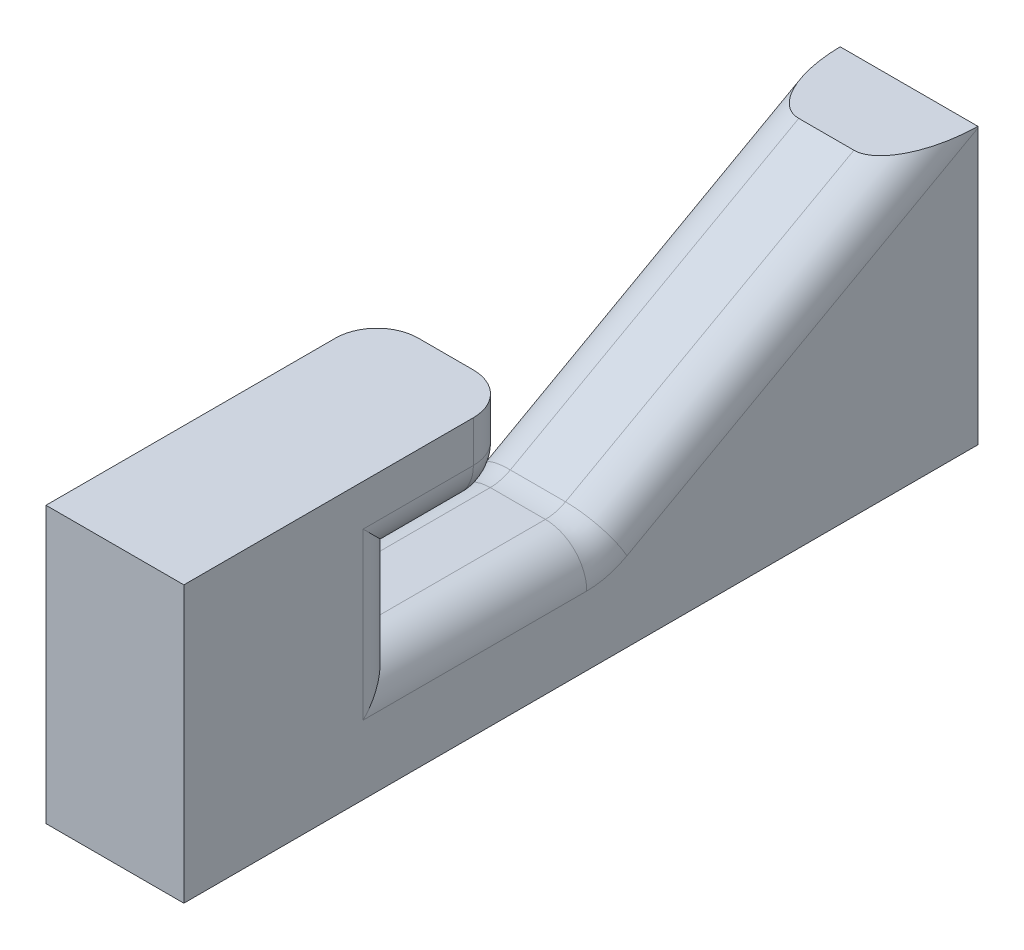
SolidWorks part; units mm, degrees
ref_plane "Front Plane" through (0, 0, 0) normal (1, 0, 0) x (0, 1, 0)
ref_plane "Top Plane" through (0, 0, 0) normal (0, 0, 1) x (0, 1, 0)
ref_plane "Right Plane" through (0, 0, 0) normal (0, 1, 0) x (-1, 0, 0)
sketch "Sketch2" plane through (0, 0, 0) normal (1, 0, 0) x (0, 1, 0)
  line L1 (0, 0) -> (10, 0)
  line L2 (0, 0) -> (0, 28.8)
  line L3 (0, 28.8) -> (10, 28.8)
  line L4 (10, 0) -> (10, 28.8)
  dimension "D1" = 28.8
  dimension "D2" = 10
extrude "Boss-Extrude1" add sketch "Sketch2" along normal blind 5
sketch "Sketch3" plane through (5, 0, 0) normal (1, 0, 0) x (0, 1, 0)
  line L0 (4, 16.8) -> (4, 13.8)
  line L1 (10, 28.8) -> (7, 28.8)
  line L2 (10, 28.8) -> (10, 16.8)
  line L3 (10, 16.8) -> (7, 16.8)
  line L4 (7, 28.8) -> (7, 16.8)
  line L5 (7, 16.8) -> (4, 16.8)
  line L6 (7, 16.8) -> (7, 20.8)
  line L7 (7, 20.8) -> (4, 20.8)
  line L8 (4, 16.8) -> (4, 20.8)
  line L10 (4, 13.8) -> (10, 3)
  line L11 (10, 0) -> (10, 28.8) construction
  line L12 (0, 0) -> (10, 0) construction
  line L13 (10, 3) -> (10, 16.8)
  line M12 (10, 0) -> (10, 28.8)
  dimension "D1" = 12
  dimension "D2" = 3
  dimension "D3" = 3
  dimension "D4" = 4
  dimension "D5" = 3
  dimension "D6" = 3
extrude "Cut-Extrude1" cut sketch "Sketch3" against normal through all contours L8 L5 L4 L7 | L0 L10 L3 L5 M12
fillet "Fillet2" radius 1.5 12 edges at (2.5, 7, 16.8) (5, 7, 18.8) (5, 4, 17.3) (5, 5.5, 20.8) (0, 4, 17.3) (0, 5.5, 20.8) (0, 7, 18.8) (0, 7, 8.4) (5, 7, 8.4) (2.5, 4, 13.8) (0, 8.5, 16.8) (5, 8.5, 16.8)
equation "\"whitekey_cutout_length\"= 101.5"
equation "\"wall_thickness\"=10"
equation "\"base_mount_height\"=40"
equation "\"base_rear_length\"=80"
equation "\"D1@Sketch2\"=\"base_mount_height\"-11-0.2"
equation "\"key_mount_recess_length\"=50"
equation "\"key_mount_recess_height\"=12.5"
equation "\"key_mount_recess_depth\"=1.5"
equation "\"guide_brace_height\"=20"
equation "\"guide_brace_thickness\"=2"
equation "\"dowel_recess_depth\"=10"
equation "\"dowel_recess_offset\"=3.25"
equation "\"base_front_length\"=111.5"
equation "\"screw_hole_wall_offset\"=7.25"
equation "\"screw_hole_edge_inset\"=\"dowel_recess_depth\"/2"
equation "\"screw_hole_diameter\"=3.8"
equation "\"screw_head_hole_diameter\"=6.7"
equation "\"screw_nut_hole_side_len\"=3.5"
equation "\"screw_shaft_diameter\"=3.5"
equation "\"switch_board_width\"=30"
equation "\"heatset_insert_hole_diameter\"=4.8"
equation "\"heatset_insert_hole_depth\"=3.8"
